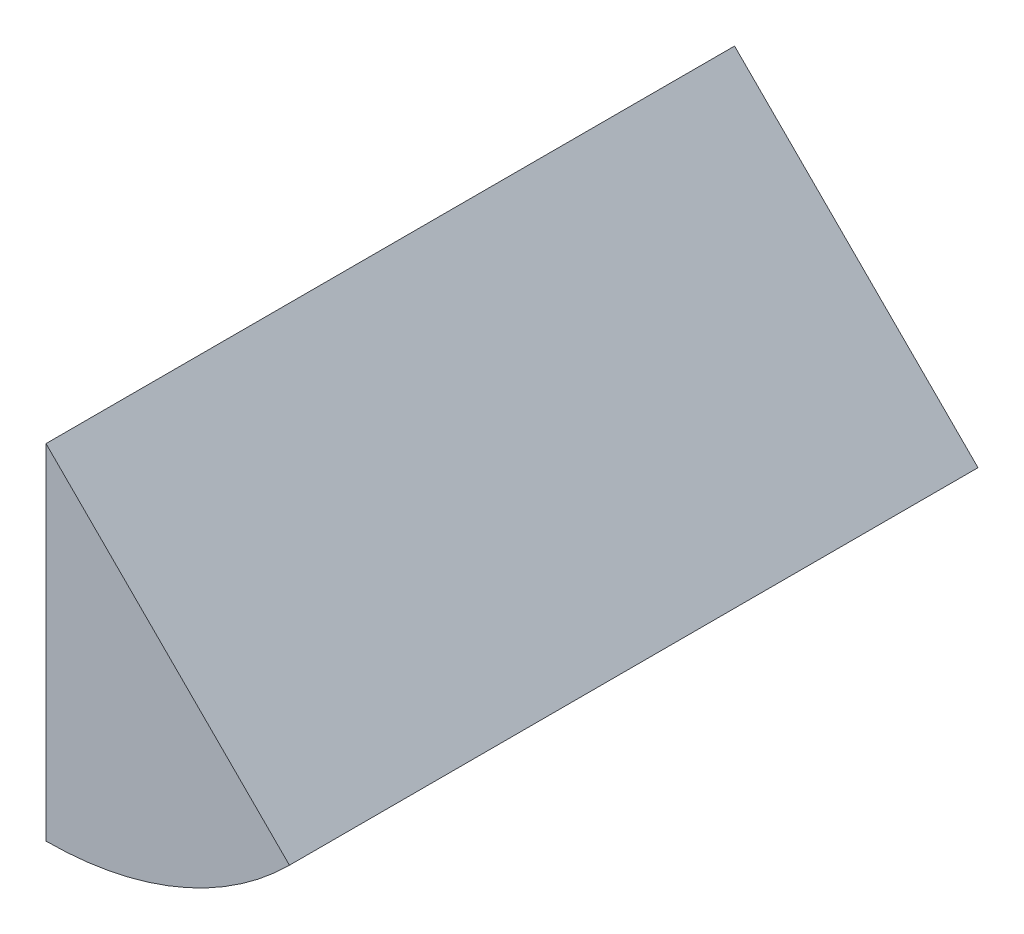
SolidWorks part; units mm, degrees
ref_plane "Alzado" through (0, 0, 0) normal (0, 0, 1) x (1, 0, 0)
ref_plane "Planta" through (0, 0, 0) normal (0, 1, 0) x (1, 0, 0)
ref_plane "Vista lateral" through (0, 0, 0) normal (1, 0, 0) x (0, 0, -1)
sketch "Croquis1" plane through (0, 0, 0) normal (0, 0, 1) x (1, 0, 0)
  line L0 (0, 0) -> (0, -25)
  line L2 (0, 0) -> (17.6777, -17.6777)
  arc A0 (0, -25) -> (17.6777, -17.6777) centre (0, 0) ccw
  dimension "D1" = 50
extrude "Saliente-Extruir1" add sketch "Croquis1" along normal blind 50
sketch "Croquis2" plane through (0, 0, 0) normal (0, 0, -1) x (-1, 0, 0)
  circle A0 centre (-6.7532, -16.4372) radius 5
  dimension "D1" = 10
extrude "Cortar-Extruir1" cut sketch "Croquis2" against normal blind 10 contours A0
